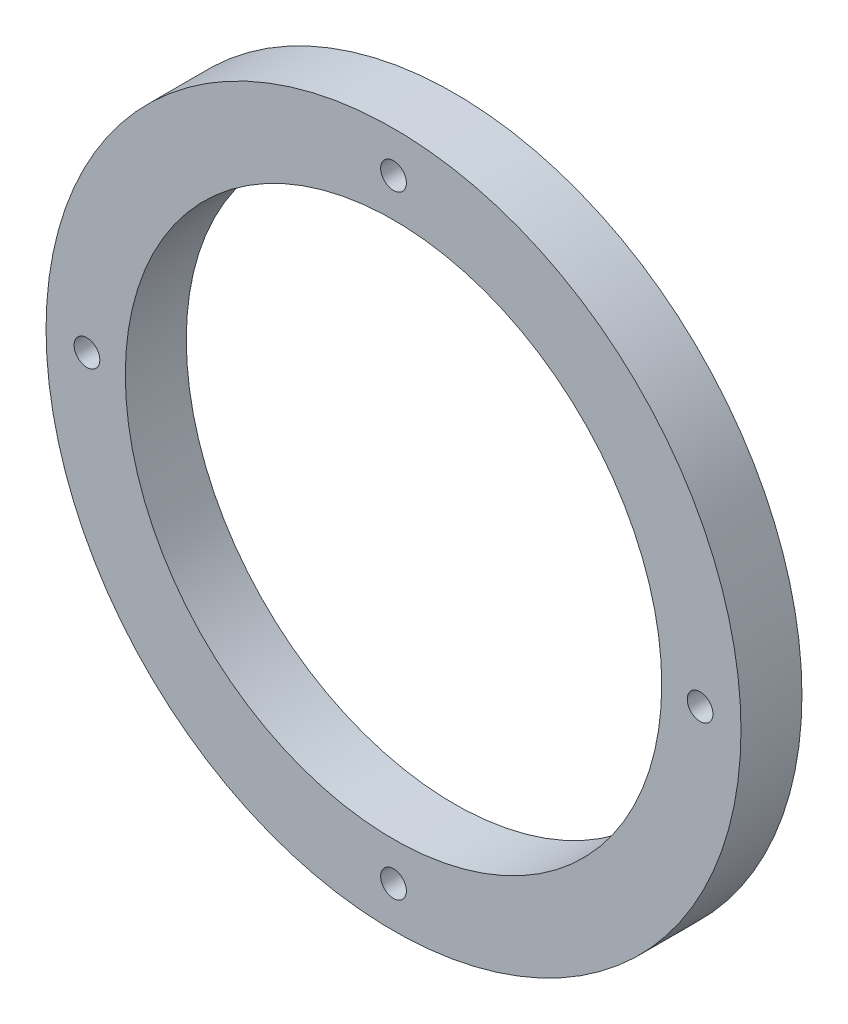
SolidWorks part; units mm, degrees
ref_plane "Front Plane" through (0, 0, 0) normal (0, 0, 1) x (1, 0, 0)
ref_plane "Top Plane" through (0, 0, 0) normal (0, 1, 0) x (1, 0, 0)
ref_plane "Right Plane" through (0, 0, 0) normal (1, 0, 0) x (0, 0, -1)
sketch "Sketch1" plane through (0, 0, 0) normal (0, 0, 1) x (1, 0, 0)
  circle A0 centre (0, 0) radius 57
extrude "Boss-Extrude1" add sketch "Sketch1" along normal blind 10
sketch "Sketch2" plane through (0, 0, 10) normal (0, 0, 1) x (1, 0, 0)
  circle A0 centre (0, 0) radius 44
extrude "Cut-Extrude1" cut sketch "Sketch2" against normal blind 10
sketch "Sketch3" plane through (0, 0, 10) normal (0, 0, 1) x (1, 0, 0)
  circle A0 centre (-50.2901, 0) radius 2.1105
  circle A1 centre (0, 50.2901) radius 2.1105
  circle A2 centre (50.2901, 0) radius 2.1105
  circle A3 centre (0, -50.2901) radius 2.1105
  point P11 (0, 0)
  dimension "D1" = 4
extrude "Cut-Extrude2" cut sketch "Sketch3" against normal blind 10
